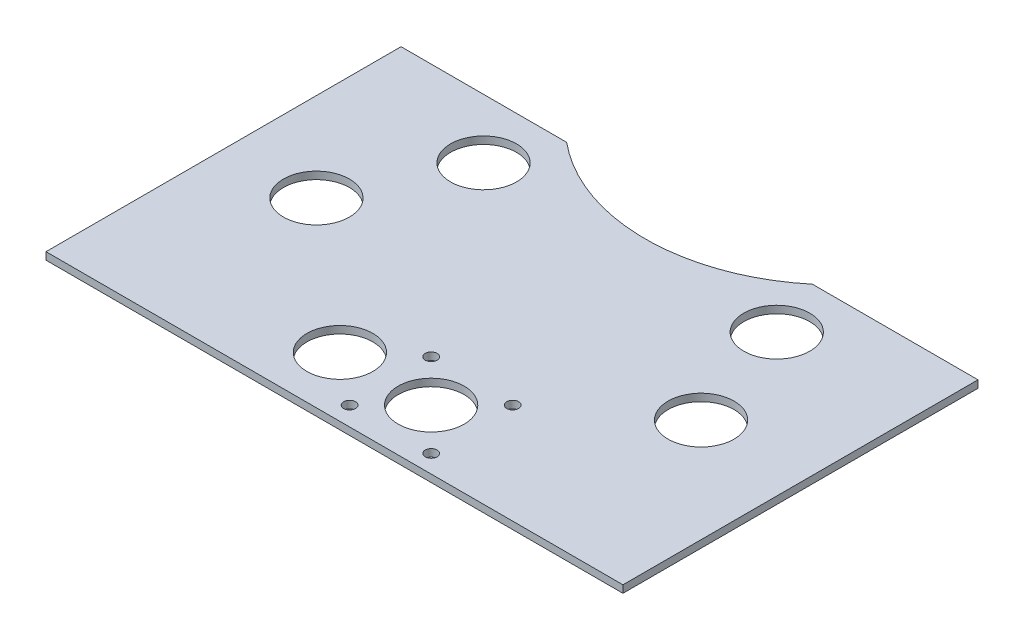
SolidWorks part; units mm, degrees
ref_plane "Front" through (0, 0, 0) normal (0, 0, 1) x (1, 0, 0)
ref_plane "Top" through (0, 0, 0) normal (0, 1, 0) x (1, 0, 0)
ref_plane "Right" through (0, 0, 0) normal (1, 0, 0) x (0, 0, -1)
sketch "Sketch1" plane through (0, 0, 0) normal (0, 1, 0) x (1, 0, 0)
  line L0 (-123.825, -55.88) -> (123.825, -55.88)
  line L1 (123.825, -55.88) -> (123.825, 96.52)
  line L2 (123.825, 96.52) -> (52.7471, 96.52)
  line L3 (-123.825, -55.88) -> (-123.825, 96.52)
  line L4 (-123.825, 96.52) -> (-52.7471, 96.52)
  arc A0 (-52.7471, 96.52) -> (52.7471, 96.52) centre (0, 160.02) ccw
  point P8 (0, -55.88)
  dimension "D1" = 165.1
  dimension "D2" = 152.4
  dimension "D3" = 247.65
  dimension "D4" = 63.5
  dimension "D5" = 55.88
extrude "Boss-Extrude1" add sketch "Sketch1" along normal blind 3.175 contours A0 L2 L1 L0 L3 L4
hole_wizard "1 (1.115) Dowel Hole1" positions "Sketch2" profile "Sketch3" hole size "1" standard "ANSI Inch" end condition through all
sketch "Sketch2" plane through (0, 3.175, 0) normal (0, 1, 0) x (1, 0, 0)
  circle A0 centre (15.875, -30.2569) radius 6.35 construction
  point P0 (15.875, -30.2569)
sketch "Sketch3" plane through (15.875, 3.175, 30.2569) normal (1, 0, 0) x (0, 0, 1)
  line L0 (0, 0) -> (0, 3.175)
  line L1 (0, 3.175) -> (14.1605, 3.175)
  line L2 (14.1605, 3.175) -> (14.1605, 0)
  line L5 (14.1605, 0) -> (0, 0)
  line L11 (0, -6.35) -> (0, 107.95) construction
  dimension "Thru Hole Dia." = 28.321
  dimension "Thru Hole Depth" = 3.175
hole_wizard "#10 Clearance Hole1" positions "Sketch4" profile "Sketch6" hole size "#10" standard "ANSI Inch" end condition up to next
sketch "Sketch4" plane through (0, 3.175, 0) normal (0, 1, 0) x (1, 0, 0)
  circle A0 centre (-1.625, -47.7569) radius 2.5527 construction
  circle A1 centre (33.375, -12.7569) radius 2.5527 construction
  circle A2 centre (33.8355, -48.2175) radius 2.5527 construction
  circle A3 centre (-2.0855, -12.2964) radius 2.5527 construction
  point P16 (-1.625, -47.7569)
  point P18 (33.375, -12.7569)
  point P25 (-2.0855, -12.2964)
  point P27 (33.8355, -48.2175)
sketch "Sketch6" plane through (-1.625, 3.175, 47.7569) normal (1, 0, 0) x (0, 0, 1)
  line L0 (0, 0) -> (0, 3.175)
  line L1 (0, 3.175) -> (2.5527, 3.175)
  line L2 (2.5527, 3.175) -> (2.5527, 0)
  line L5 (2.5527, 0) -> (0, 0)
  line L11 (0, -6.35) -> (0, 107.95) construction
  dimension "Thru Hole Dia." = 5.1054
  dimension "Thru Hole Depth" = 3.175
fillet "Fillet1" [suppressed] radius 38.1
hole_wizard "1 (1.115) Dowel Hole3" positions "Sketch9" profile "Sketch10" hole size "1" standard "ANSI Inch" end condition through all
sketch "Sketch9" plane through (-3.175, -34.925, 0) normal (0, -1, 0) x (-1, 0, 0)
  line L0 (82.55, 22.098) -> (-82.55, 22.098) construction
  point P0 (82.55, 22.098)
  point P2 (-82.55, 22.098)
sketch "Sketch10" plane through (-85.725, -34.925, -22.098) normal (1, 0, 0) x (0, 0, -1)
  line L0 (0, 0) -> (0, 38.1)
  line L1 (0, 38.1) -> (14.1605, 38.1)
  line L2 (14.1605, 38.1) -> (14.1605, 0)
  line L3 (14.1605, 0) -> (0, 0)
  line L4 (0, -6.35) -> (0, 107.95) construction
  dimension "Thru Hole Dia." = 28.321
  dimension "Thru Hole Depth" = 38.1
sketch "Sketch11" plane through (0, 3.175, 0) normal (0, 1, 0) x (1, 0, 0)
  line L0 (-23.3045, -30.2569) -> (30.0355, -30.2569) construction
  line L1 (-123.825, -55.88) -> (123.825, -55.88) construction
  circle A0 centre (-23.3045, -30.2569) radius 14.1605
  circle A1 centre (15.875, -30.2569) radius 14.1605 construction
  point P8 (-45.1916, -30.2569)
  dimension "D1" = 28.321
  dimension "D2" = 53.34
extrude "Cut-Extrude1" cut sketch "Sketch11" against normal through all
sketch "Sketch12" plane through (0, 3.175, 0) normal (0, 1, 0) x (1, 0, 0)
  circle A0 centre (-62.9335, 71.035) radius 14.1605
  dimension "D1" = 28.321
extrude "Cut-Extrude2" cut sketch "Sketch12" against normal through all
mirror "Mirror2" about plane through (0, 0, 0) normal (1, 0, 0) of "Cut-Extrude2"
